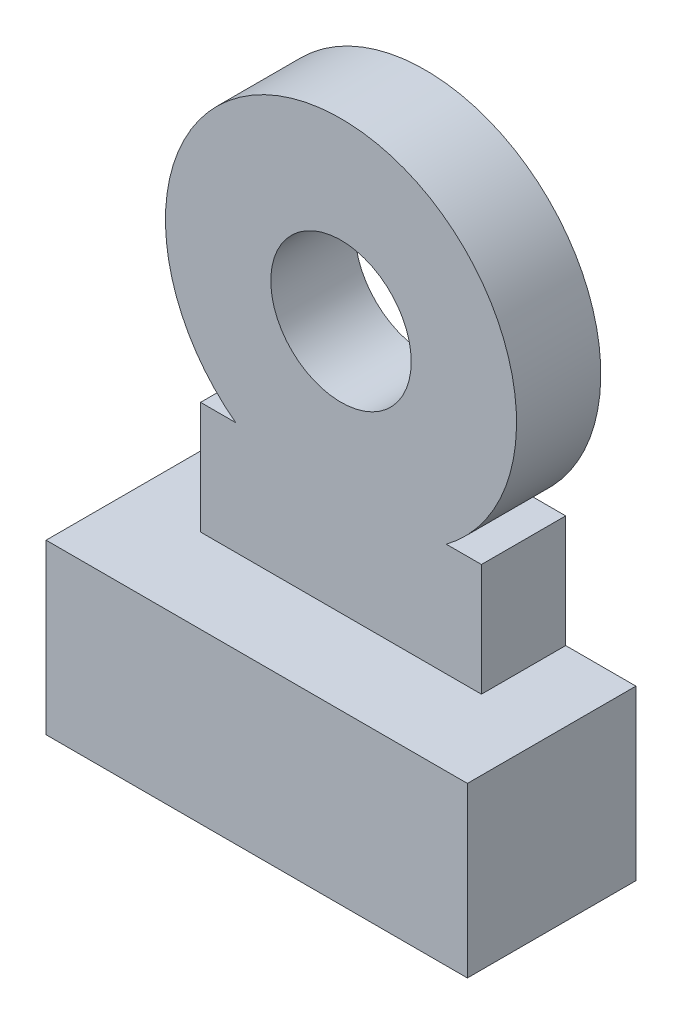
SolidWorks part; units mm, degrees
ref_plane "前基準面" through (0, 0, 0) normal (0, 0, 1) x (1, 0, 0)
ref_plane "上基準面" through (0, 0, 0) normal (0, 1, 0) x (1, 0, 0)
ref_plane "右基準面" through (0, 0, 0) normal (1, 0, 0) x (0, 0, -1)
sketch "草圖1" plane through (0, 0, 0) normal (0, 1, 0) x (1, 0, 0)
  line L1 (-3, 1.2) -> (3, 1.2)
  line L2 (-3, 1.2) -> (-3, -1.2)
  line L3 (-3, -1.2) -> (3, -1.2)
  line L4 (3, 1.2) -> (3, -1.2)
  line L5 (-3, 1.2) -> (3, -1.2) construction
  line L6 (-3, -1.2) -> (3, 1.2) construction
  point P0 (0, 0)
  dimension "D1" = 2.4
  dimension "D2" = 6
extrude "伸長1" add sketch "草圖1" along normal blind 2.4
sketch "草圖2" plane through (0, 0, 0) normal (0, 0, 1) x (1, 0, 0)
  line L0 (-3, 0) -> (-3, 8.7224) construction
  line L1 (-3, 2.4) -> (3, 2.4) construction
  line L2 (-2, 4) -> (-1.5, 4)
  line L3 (-2, 4) -> (-2, 2.4)
  line L4 (-2, 2.4) -> (2, 2.4)
  line L5 (2, 4) -> (2, 2.4)
  line L6 (-2, 4) -> (2, 2.4) construction
  line L7 (-2, 2.4) -> (2, 4) construction
  line L8 (0, 0) -> (0, 6) construction
  line L9 (1.5, 4) -> (2, 4)
  arc A0 (1.5, 4) -> (-1.5, 4) centre (0, 6) ccw
  point P5 (0, 3.2)
  dimension "D1" = 5
  dimension "D2" = 6
  dimension "D3" = 4
  dimension "D4" = 1.6
extrude "伸長3" add sketch "草圖2" against normal blind 1.2 separate body
sketch "草圖4" plane through (0, 0, 0) normal (0, 0, 1) x (1, 0, 0)
  circle A0 centre (0, 6) radius 1
  dimension "D1" = 2
extrude "伸長4" cut sketch "草圖4" against normal blind 1.2
